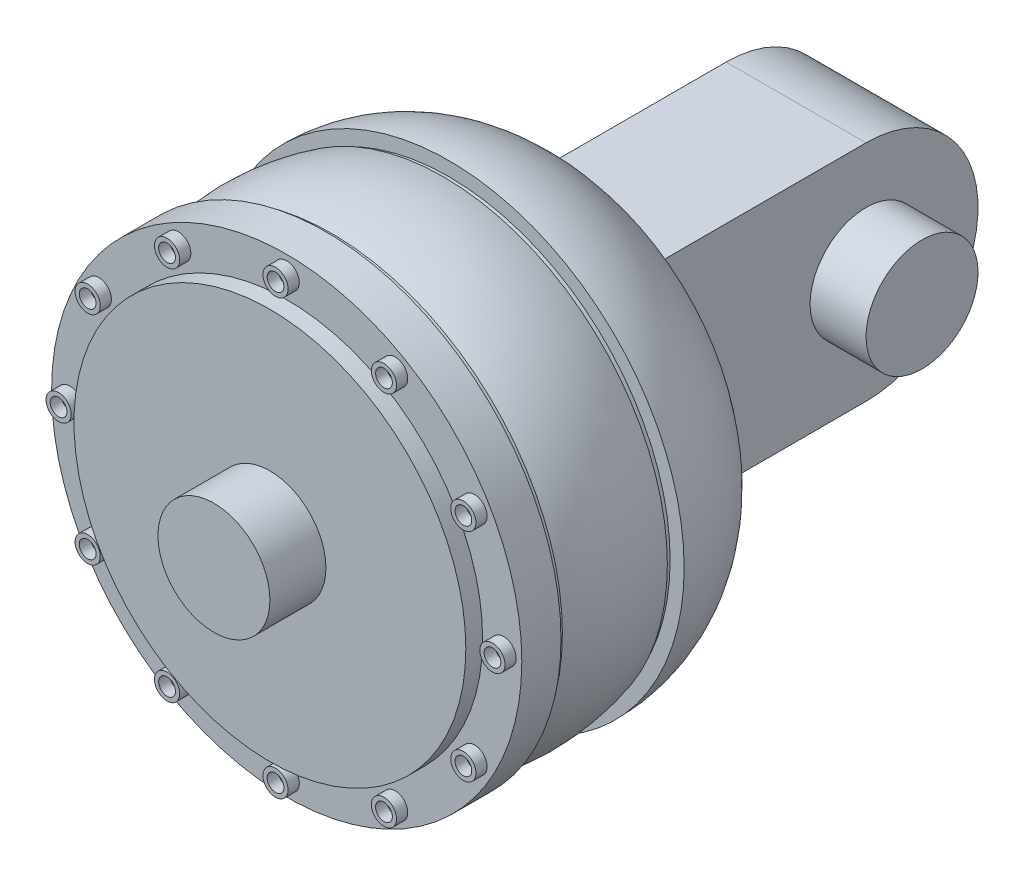
SolidWorks part; units mm, degrees
ref_plane "Front Plane" through (0, 0, 0) normal (0, 0, 1) x (1, 0, 0)
ref_plane "Top Plane" through (0, 0, 0) normal (0, 1, 0) x (1, 0, 0)
ref_plane "Right Plane" through (0, 0, 0) normal (1, 0, 0) x (0, 0, -1)
sketch "Sketch1" plane through (0, 0, 0) normal (0, 1, 0) x (1, 0, 0)
  line L0 (224.3348, 380.1217) -> (908.8611, 380.1217) construction
  line L1 (-42, 0) -> (0, 0)
  line L2 (0, 0) -> (0, 20)
  line L3 (0, 20) -> (-32, 20)
  arc A0 (-42, 0) -> (-32, 20) centre (-17, 0) cw
  dimension "D4" = 25
  dimension "D1" = 42
  dimension "D2" = 20
  dimension "D3" = 32
revolve "Revolve1" add sketch "Sketch1" angle 360 about L2
sketch "Sketch2" plane through (0, 0, 0) normal (0, 0, 1) x (1, 0, 0)
  circle A0 centre (0, 0) radius 39.5
  dimension "D1" = 79
extrude "Boss-Extrude1" add sketch "Sketch2" along normal blind 1
sketch "Sketch3" plane through (0, 0, 0) normal (0, 1, 0) x (1, 0, 0)
  line L0 (0, -1) -> (0, -21)
  line L1 (-39.5, -1) -> (39.5, -1) construction
  line L2 (0, -21) -> (-40, -21)
  line L3 (0, -1) -> (-40, -1)
  arc A0 (-40, -21) -> (-40, -1) centre (-4.377, -11) cw
  dimension "D4" = 37
  dimension "D1" = 20
  dimension "D2" = 40
  dimension "D3" = 40
revolve "Revolve2" add sketch "Sketch3" angle 360 about L0
sketch "Sketch4" plane through (0, 0, 21) normal (0, 0, 1) x (1, 0, 0)
  circle A0 centre (0, 0) radius 41.25
  dimension "D1" = 82.5
extrude "Boss-Extrude2" add sketch "Sketch4" along normal blind 1
sketch "Sketch5" plane through (0, 0, 22) normal (0, 0, 1) x (1, 0, 0)
  circle A0 centre (0, 0) radius 42
  dimension "D1" = 84
extrude "Boss-Extrude3" add sketch "Sketch5" along normal blind 7
sketch "Sketch6" plane through (0, 0, 29) normal (0, 0, 1) x (1, 0, 0)
  circle A0 centre (0, 0) radius 35
  dimension "D1" = 70
extrude "Boss-Extrude4" add sketch "Sketch6" along normal blind 3
sketch "Sketch7" plane through (0, 0, 29) normal (0, 0, 1) x (1, 0, 0)
  line L0 (0, 0) -> (42, 0) construction
  circle A0 centre (0, 0) radius 42 construction
  circle A1 centre (38.75, 0) radius 2.25
  circle A2 centre (38.75, 0) radius 1.5
  dimension "D2" = 4.5
  dimension "D3" = 3
  dimension "D1" = 3.25
extrude "Boss-Extrude5" add sketch "Sketch7" along normal blind 2
pattern_circular "CirPattern1" count 12 over 360 about axis through (0, 0, 0) along (0, 0, 1) of "Boss-Extrude5"
sketch "Sketch8" plane through (0, 0, -20) normal (0, 0, -1) x (-1, 0, 0)
  line L1 (-12.5, 20) -> (12.5, 20)
  line L2 (-12.5, 20) -> (-12.5, -20)
  line L3 (-12.5, -20) -> (12.5, -20)
  line L4 (12.5, 20) -> (12.5, -20)
  line L5 (-12.5, 20) -> (12.5, -20) construction
  line L6 (-12.5, -20) -> (12.5, 20) construction
  point P0 (0, 0)
  dimension "D1" = 25
  dimension "D2" = 40
extrude "Boss-Extrude6" add sketch "Sketch8" along normal blind 42
sketch "Sketch9" plane through (-12.5, 0, 0) normal (-1, 0, 0) x (0, 0, 1)
  line L0 (-62, -20) -> (-62, 20) construction
  circle A0 centre (-62, 0) radius 20
extrude "Boss-Extrude7" add sketch "Sketch9" against normal up to surface (25 mm away) up to face at (12.5, 0, -41)
sketch "Sketch10" plane through (-12.5, 0, 0) normal (-1, 0, 0) x (0, 0, 1)
  circle A0 centre (-62, 0) radius 10
  dimension "D1" = 20
extrude "Boss-Extrude8" add sketch "Sketch10" along normal blind 10
mirror "Mirror1" about plane through (0, 0, 0) normal (1, 0, 0) of "Boss-Extrude8"
sketch "Sketch11" plane through (0, 0, 32) normal (0, 0, 1) x (1, 0, 0)
  circle A0 centre (0, 0) radius 10
  dimension "D1" = 20
extrude "Boss-Extrude9" add sketch "Sketch11" along normal blind 10
